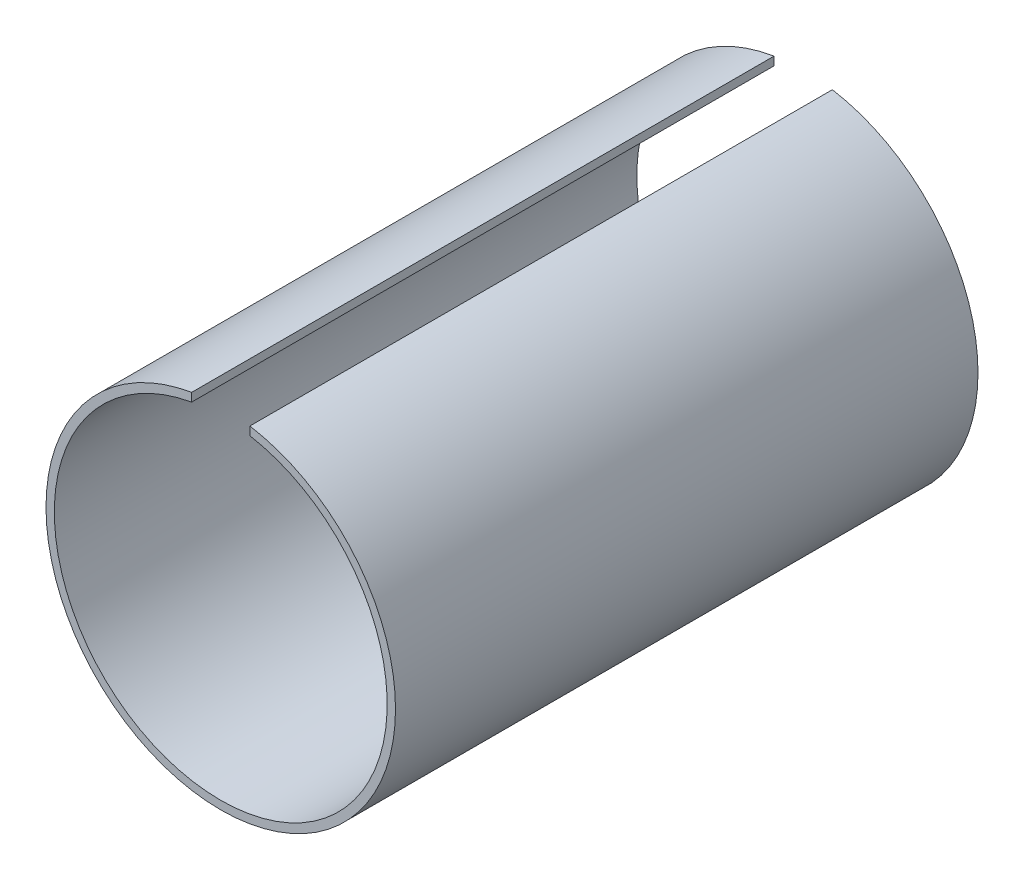
SolidWorks part; units mm, degrees
material "铜"
ref_plane "前视基准面" through (0, 0, 0) normal (0, 0, 1) x (1, 0, 0)
ref_plane "上视基准面" through (0, 0, 0) normal (0, 1, 0) x (1, 0, 0)
ref_plane "右视基准面" through (0, 0, 0) normal (1, 0, 0) x (0, 0, -1)
sketch "草图1" plane through (0, 0, 0) normal (0, 0, 1) x (1, 0, 0)
  circle A0 centre (0, 0) radius 20
  dimension "D1" = 40
extrude "拉伸-薄壁1" add sketch "草图1" along normal mid plane 70 thin
sketch "草图2" plane through (0, 0, 35) normal (0, 0, 1) x (1, 0, 0)
  line L0 (0, 0) -> (0, 27.3648)
extrude "切除-拉伸-薄壁1" cut sketch "草图2" against normal through all thin thin type mid plane wall 7
